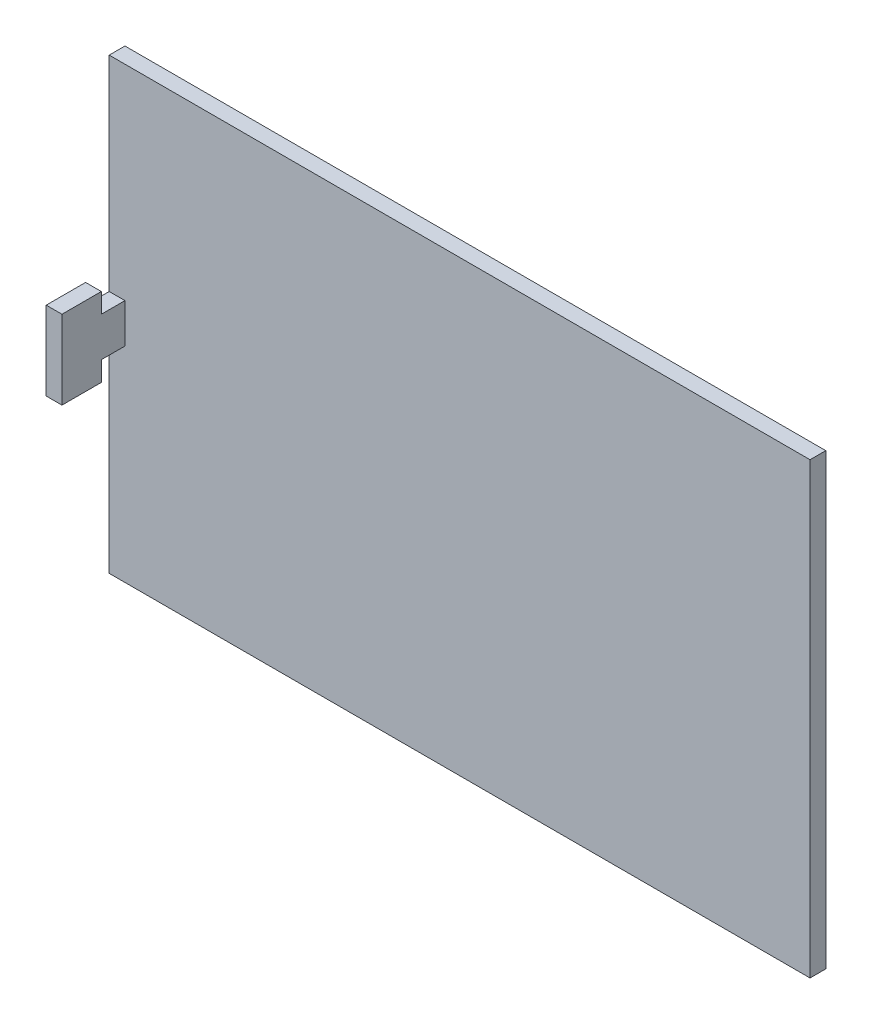
SolidWorks part; units mm, degrees
ref_plane "Plan de face" through (0, 0, 0) normal (0, 0, 1) x (1, 0, 0)
ref_plane "Plan de dessus" through (0, 0, 0) normal (0, 1, 0) x (1, 0, 0)
ref_plane "Plan de droite" through (0, 0, 0) normal (1, 0, 0) x (0, 0, -1)
sketch "Esquisse1" plane through (0, 0, 0) normal (0, 0, 1) x (1, 0, 0)
  line L1 (-75.6383, 24.3371) -> (13.3617, 24.3371)
  line L2 (-75.6383, 24.3371) -> (-75.6383, -32.6629)
  line L3 (-75.6383, -32.6629) -> (13.3617, -32.6629)
  line L4 (13.3617, 24.3371) -> (13.3617, -32.6629)
  dimension "D1" = 57
  dimension "D2" = 89
extrude "Boss.-Extru.1" add sketch "Esquisse1" along normal blind 2
sketch "Esquisse2" plane through (0, 0, 2) normal (0, 0, 1) x (1, 0, 0)
  line L0 (-75.6383, -4.1629) -> (13.3617, -4.1629) construction
  line L1 (-75.6383, 24.3371) -> (-75.6383, -32.6629) construction
  line L2 (13.3617, -32.6629) -> (13.3617, 24.3371) construction
  line L3 (-74.6383, -6.6629) -> (-74.6383, -4.1629) construction
  line L4 (-75.6383, -1.6629) -> (-73.6383, -1.6629)
  line L5 (-75.6383, -1.6629) -> (-75.6383, -6.6629)
  line L6 (-75.6383, -6.6629) -> (-73.6383, -6.6629)
  line L7 (-73.6383, -1.6629) -> (-73.6383, -6.6629)
  dimension "D1" = 5
  dimension "D2" = 2
extrude "Boss.-Extru.2" add sketch "Esquisse2" along normal blind 3
sketch "Esquisse3" plane through (0, 0, 5) normal (0, 0, 1) x (1, 0, 0)
  line L0 (-75.6383, 24.3371) -> (-75.6383, -1.6629) construction
  line L1 (-75.6383, 0.8371) -> (-73.6383, 0.8371)
  line L2 (-75.6383, 0.8371) -> (-75.6383, -9.1629)
  line L3 (-75.6383, -9.1629) -> (-73.6383, -9.1629)
  line L4 (-73.6383, 0.8371) -> (-73.6383, -9.1629)
  line L5 (-75.6383, -9.1629) -> (-75.6383, -6.6629) construction
  line L9 (-75.6383, -9.1629) -> (-75.6383, -6.6629) construction
  dimension "D1" = 10
  dimension "D2" = 2
extrude "Boss.-Extru.3" add sketch "Esquisse3" along normal blind 5
